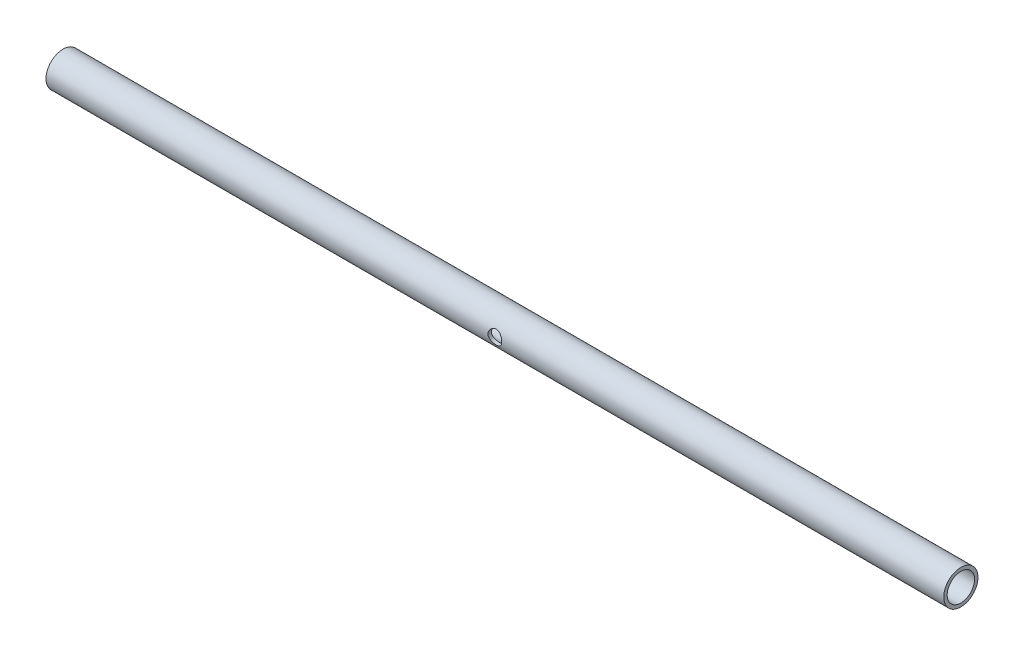
SolidWorks part; units mm, degrees
material "Hexcel AS4C (3000 Filaments)"
ref_plane "前基準面" through (0, 0, 0) normal (0, 0, 1) x (1, 0, 0)
ref_plane "上基準面" through (0, 0, 0) normal (0, 1, 0) x (1, 0, 0)
ref_plane "右基準面" through (0, 0, 0) normal (1, 0, 0) x (0, 0, -1)
sketch "草圖1" plane through (0, 0, 0) normal (1, 0, 0) x (0, 0, -1)
  circle A0 centre (0, 0) radius 5
  circle A1 centre (0, 0) radius 4
  dimension "D1" = 10
  dimension "D2" = 1
extrude "填料-伸長1" add sketch "草圖1" along normal mid plane 262
sketch "草圖2" plane through (0, 0, 0) normal (0, 0, 1) x (1, 0, 0)
  circle A0 centre (0, 0) radius 2
  dimension "D1" = 4
extrude "除料-伸長1" cut sketch "草圖2" against normal through all both and the other way through all contours A0
